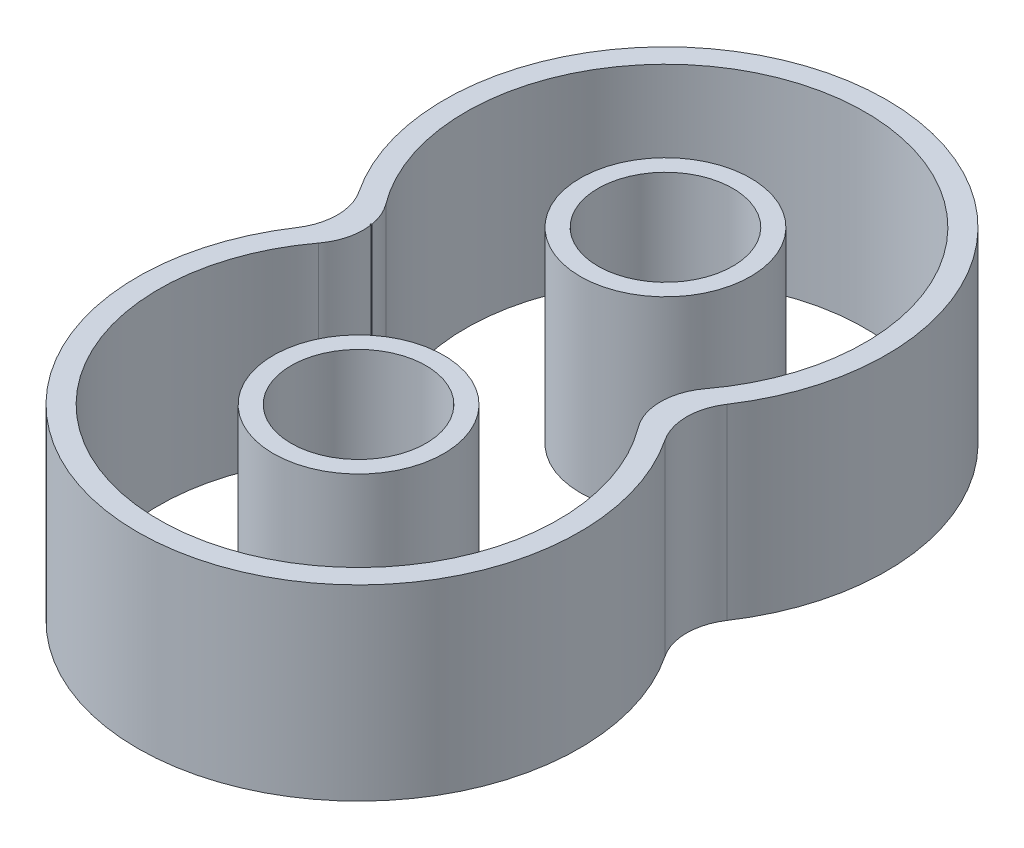
SolidWorks part; units mm, degrees
ref_plane "Front Plane" through (0, 0, 0) normal (0, 0, 1) x (1, 0, 0)
ref_plane "Top Plane" through (0, 0, 0) normal (0, 1, 0) x (1, 0, 0)
ref_plane "Right Plane" through (0, 0, 0) normal (1, 0, 0) x (0, 0, -1)
sketch "Sketch8" plane through (0, 0, 0) normal (0, 1, 0) x (1, 0, 0)
  line L0 (-247.7238, 4.416) -> (247.7238, 4.416) construction
  line L1 (-1.9828, 81.9318) -> (-1.9828, 188.5806)
  line L2 (-1.9828, -81.9318) -> (-1.9828, -188.5806)
  circle A8 centre (-1.9828, 81.9318) radius 45.5
  circle A9 centre (-1.9828, 81.9318) radius 36
  circle A10 centre (-1.9828, -81.9318) radius 45.5
  circle A11 centre (-1.9828, -81.9318) radius 36
  arc A12 (83.3699, 17.9874) -> (-87.3356, 17.9874) centre (-1.9828, 81.9318) ccw
  arc A13 (96.3084, 16.6056) -> (-100.2741, 16.6056) centre (-1.9828, 81.9318) ccw
  arc A14 (-87.3356, -17.9874) -> (83.3699, -17.9874) centre (-1.9828, -81.9318) ccw
  arc A15 (-78.6493, 7.7952) -> (-82.4362, 4.416) centre (-1.9828, -81.9318) ccw
  arc A16 (-100.2741, -16.6056) -> (96.3084, -16.6056) centre (-1.9828, -81.9318) ccw
  arc A17 (96.3084, -16.6056) -> (96.3084, 16.6056) centre (121.2935, 0) cw
  arc A18 (83.3699, 17.9874) -> (83.3699, -17.9874) centre (107.3794, 0) ccw
  arc A19 (-100.2741, 16.6056) -> (-100.2741, -16.6056) centre (-125.2592, 0) cw
  arc A20 (-87.3356, 17.9874) -> (-87.3356, -17.9874) centre (-111.3451, 0) cw
  point P18 (-86.9291, 0)
  dimension "D1" = 91
  dimension "D2" = 72
  dimension "D3" = 91
  dimension "D4" = 72
  dimension "D5" = 30
  dimension "D6" = 106.6489
  dimension "D7" = 106.6489
extrude "Boss-Extrude1" add sketch "Sketch8" along normal blind 100
